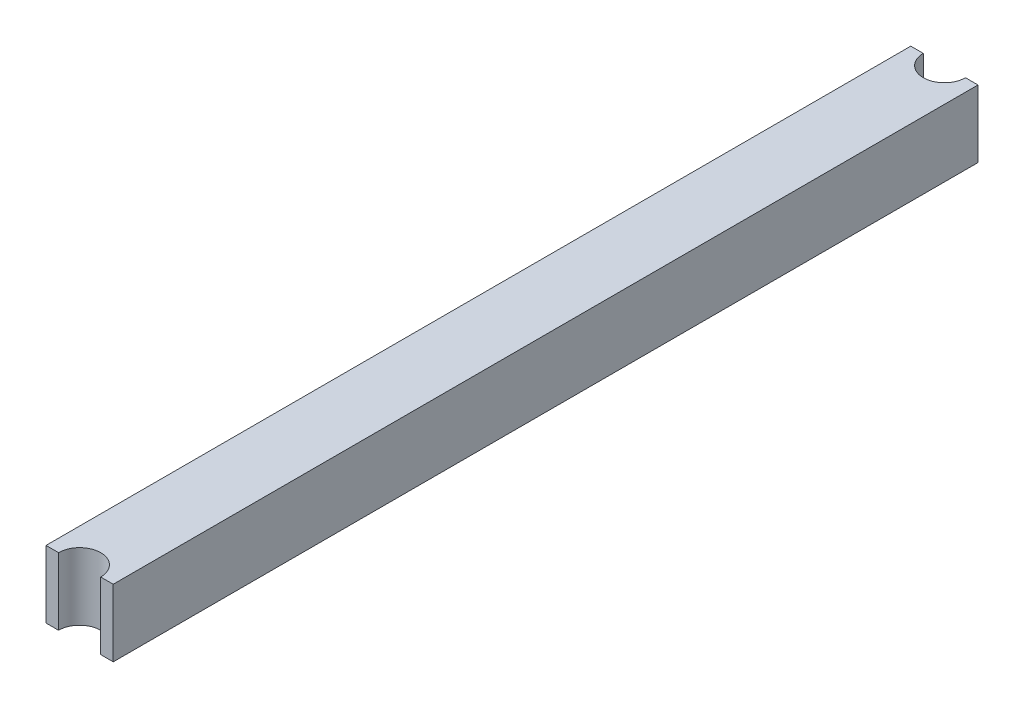
SolidWorks part; units mm, degrees
material "Plain Carbon Steel"
ref_plane "Front Plane" through (0, 0, 0) normal (0, 0, 1) x (1, 0, 0)
ref_plane "Top Plane" through (0, 0, 0) normal (0, 1, 0) x (1, 0, 0)
ref_plane "Right Plane" through (0, 0, 0) normal (1, 0, 0) x (0, 0, -1)
sketch "Sketch1" plane through (0, 0, 0) normal (0, 0, 1) x (1, 0, 0)
  line L1 (-31.1, 31.1) -> (0, 31.1)
  line L2 (-31.1, 31.1) -> (-31.1, 0)
  line L3 (-31.1, 0) -> (0, 0)
  line L4 (0, 31.1) -> (0, 0)
extrude "Boss-Extrude1" add sketch "Sketch1" along normal blind 400
sketch "Sketch2" plane through (0, 31.1, 0) normal (0, 1, 0) x (1, 0, 0)
  line L0 (0, -400) -> (-31.1, -400) construction
  line L1 (0, 0) -> (-31.1, 0) construction
  circle A0 centre (-15.55, -400) radius 9.755
  circle A1 centre (-15.55, 0) radius 9.755
extrude "Cut-Extrude1" cut sketch "Sketch2" against normal blind 31.1
